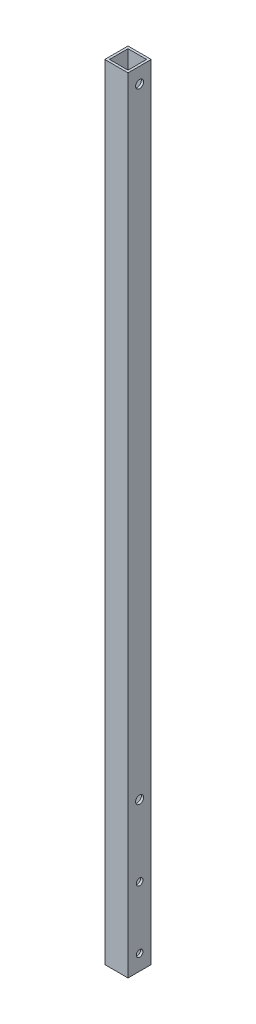
SolidWorks part; units mm, degrees
material "5052-H34"
ref_plane "正面" through (0, 0, 0) normal (0, 0, 1) x (1, 0, 0)
ref_plane "平面" through (0, 0, 0) normal (0, 1, 0) x (1, 0, 0)
ref_plane "右側面" through (0, 0, 0) normal (1, 0, 0) x (0, 0, -1)
sketch "ｽｹｯﾁ1" plane through (0, 0, 0) normal (0, 1, 0) x (1, 0, 0)
  line L1 (0, 0) -> (15, 0)
  line L2 (0, 0) -> (0, 15)
  line L3 (0, 15) -> (15, 15)
  line L4 (15, 0) -> (15, 15)
  dimension "D1" = 15
  dimension "D2" = 15
extrude "押し出し-薄板1" add sketch "ｽｹｯﾁ1" along normal blind 506 thin thin type one direction reverse wall 1.5
sketch "ｽｹｯﾁ2" plane through (15, 0, 0) normal (1, 0, 0) x (0, 0, -1)
  line L0 (7.5, 506) -> (7.5, 0) construction
  line L1 (0, 506) -> (15, 506) construction
  line L2 (0, 0) -> (15, 0) construction
  line L3 (0, 506) -> (0, 0) construction
  circle A1 centre (7.5, 256) radius 2.5 construction
  circle A2 centre (7.5, 496) radius 2.6
  circle A3 centre (7.5, 96) radius 2.15 construction
  circle A5 centre (7.5, 176) radius 2.5 construction
  circle A6 centre (7.5, 416) radius 2.5 construction
  circle A7 centre (7.5, 10) radius 2.15
  circle A9 centre (7.5, 50) radius 2.15
  circle A10 centre (7.5, 496) radius 2.5 construction
  circle A11 centre (7.5, 96) radius 2.6
  dimension "D2" = 10
  dimension "D3" = 46
  dimension "D4" = 5.2
  dimension "D5" = 80
  dimension "D6" = 4.3
  dimension "D7" = 7.5
  dimension "D8" = 80
  dimension "D9" = 416
  dimension "D10" = 5
  dimension "D11" = 10
  dimension "D12" = 5.2
  dimension "D15" = 496
  dimension "D14" = 40
extrude "ｶｯﾄ - 押し出し1" cut sketch "ｽｹｯﾁ2" against normal up to surface (15 mm away) up to face at (0, 253, -7.5)
sketch "ｽｹｯﾁ3" plane through (0, 0, 0) normal (0, 0, 1) x (1, 0, 0)
  line L0 (7.5, 506) -> (7.5, 0) construction
  line L1 (0, 506) -> (15, 506) construction
  line L2 (0, 0) -> (15, 0) construction
  circle A0 centre (7.5, 404) radius 2.15
  circle A1 centre (7.5, 374) radius 2.15
  circle A2 centre (7.5, 502.5) radius 2.15
  dimension "D1" = 4.3
  dimension "D2" = 30
  dimension "D3" = 102
  dimension "D4" = 502.5
extrude "ｶｯﾄ - 押し出し2" [suppressed] cut sketch "ｽｹｯﾁ3" against normal up to surface (15 mm away)
